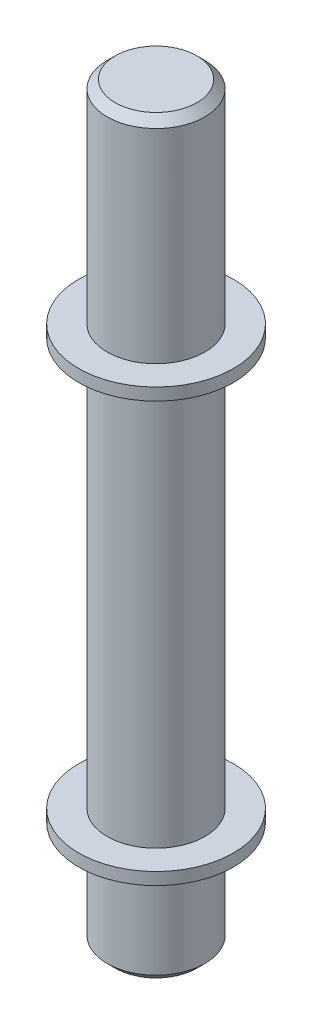
SolidWorks part; units mm, degrees
ref_plane "Front Plane" through (0, 0, 0) normal (0, 0, 1) x (1, 0, 0)
ref_plane "Top Plane" through (0, 0, 0) normal (0, 1, 0) x (1, 0, 0)
ref_plane "Right Plane" through (0, 0, 0) normal (1, 0, 0) x (0, 0, -1)
sketch "Sketch2" plane through (0, 0, 0) normal (0, 0, 1) x (1, 0, 0)
  line L0 (12, 29) -> (12, 129)
  line L1 (0, 0) -> (12, 0)
  line L2 (0, 0) -> (0, 184)
  line L3 (0, 184) -> (12, 184)
  line L4 (12, 0) -> (12, 26)
  line L5 (12, 132) -> (19, 132)
  line L7 (12, 129) -> (19, 129)
  line L8 (19, 132) -> (19, 129)
  line L9 (12, 29) -> (19, 29)
  line L11 (12, 26) -> (19, 26)
  line L12 (19, 29) -> (19, 26)
  line L13 (12, 132) -> (12, 184)
  dimension "D1" = 26
  dimension "D2" = 3
  dimension "D3" = 100
  dimension "D4" = 3
  dimension "D5" = 52
  dimension "D6" = 19
  dimension "D7" = 12
  dimension "D8" = 19
revolve "Revolve1" add sketch "Sketch2" angle 360 about L2
chamfer "Chamfer1" distance 2 angle 45 2 edges at (0, 0, -12) (0, 184, -12)
cosmetic thread "Cosmetic Thread1" parameters "D1"=21, "D2"=20.704
cosmetic thread "Cosmetic Thread2" parameters "D1"=26, "D2"=20.704
